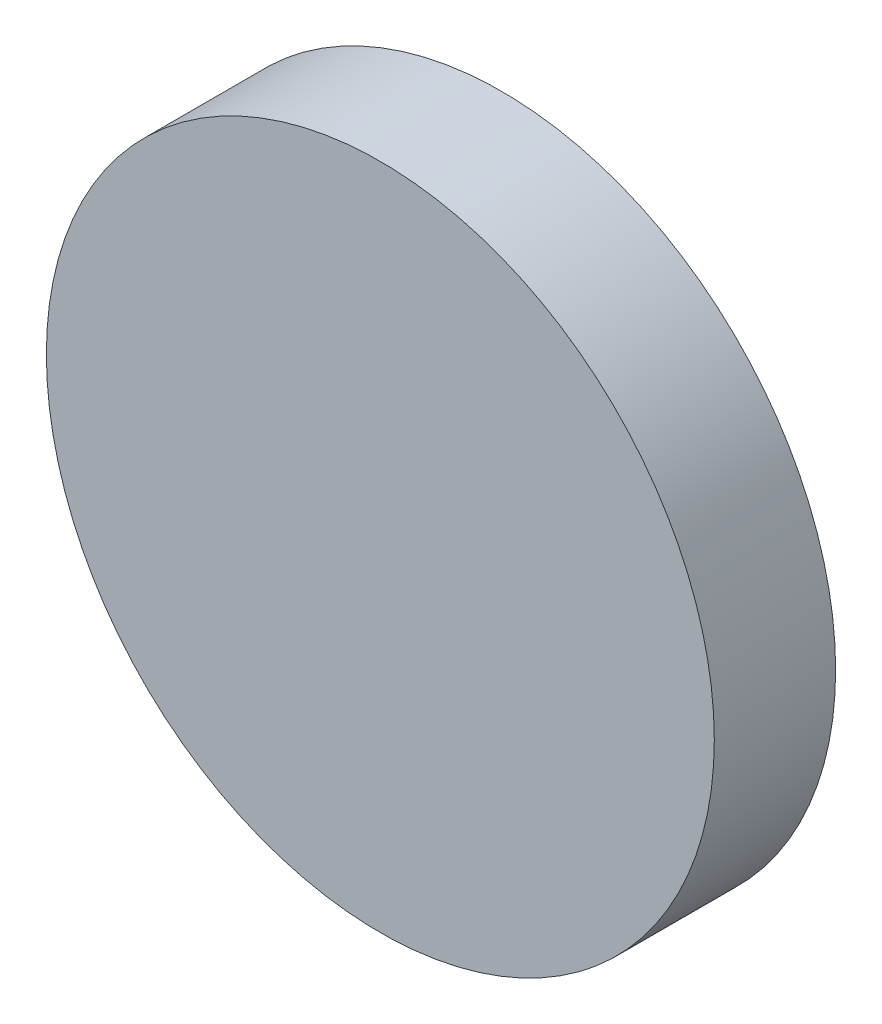
SolidWorks part; units mm, degrees
ref_plane "前视基准面" through (0, 0, 0) normal (0, 0, 1) x (1, 0, 0)
ref_plane "上视基准面" through (0, 0, 0) normal (0, 1, 0) x (1, 0, 0)
ref_plane "右视基准面" through (0, 0, 0) normal (1, 0, 0) x (0, 0, -1)
sketch "草图1" plane through (0, 0, 0) normal (0, 0, 1) x (1, 0, 0)
  circle A4 centre (0, 0) radius 27.527
extrude "凸台-拉伸1" add sketch "草图1" along normal blind 10
sketch "草图2" plane through (0, 0, 10) normal (0, 0, 1) x (1, 0, 0)
  line L0 (-49.3001, 19.7846) -> (-47.3639, -6.5287)
  line L1 (-59.2732, 19.0507) -> (-57.3369, -7.2625)
  line L2 (-39.3271, 20.5185) -> (-37.3909, -5.7948)
  circle A2 centre (0, 0) radius 32.527
  circle A3 centre (0, 0) radius 32.527
  circle A5 centre (0, 0) radius 32.527
  circle A6 centre (0, 0) radius 22.527
  circle A7 centre (0, 0) radius 22.527
  circle A8 centre (0, 0) radius 12.527
  dimension "D1" = 5
  dimension "D2" = 5
  dimension "D3" = 10
  dimension "D4" = 10
  dimension "D5" = 10
  dimension "D6" = 10
